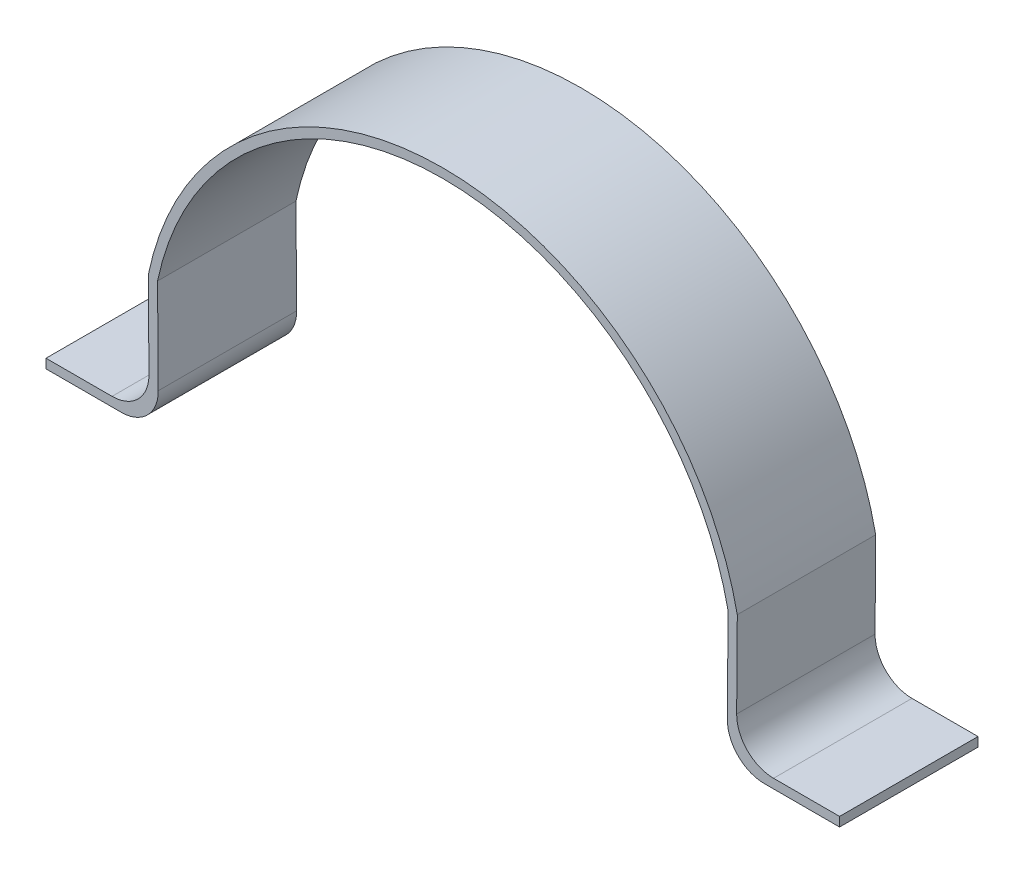
SolidWorks part; units mm, degrees
ref_plane "Спереди" through (0, 0, 0) normal (0, 0, 1) x (1, 0, 0)
ref_plane "Сверху" through (0, 0, 0) normal (0, 1, 0) x (1, 0, 0)
ref_plane "Справа" through (0, 0, 0) normal (1, 0, 0) x (0, 0, -1)
sketch "Эскиз8" plane through (0, 0, 0) normal (0, 0, 1) x (1, 0, 0)
  line L0 (-31.9184, 6.6096) -> (-31.8191, -6.7834)
  line L1 (-31.8191, -6.7834) -> (-43.0074, -6.7834)
  line L2 (0, 31.1118) -> (0, 49.2071) construction
  line L3 (31.8191, -6.7834) -> (43.0074, -6.7834)
  line L4 (31.9184, 6.6096) -> (31.8191, -6.7834)
  arc A0 (31.9184, 6.6096) -> (-31.9184, 6.6096) centre (0, 0) ccw
  circle A2 centre (0, -0.1657) radius 32.5 construction
extrude "Вытянуть-Тонкостенный1" add sketch "Эскиз8" along normal blind 15 thin thin type one direction wall 1
fillet "Скругление1" radius 4 1 edges at (-31.8191, -6.7834, 7.5)
fillet "Скругление2" radius 4 1 edges at (-30.8117, -7.7834, 7.5)
fillet "Скругление3" radius 4 2 edges at (30.8117, -7.7834, 7.5) (31.8191, -6.7834, 7.5)
